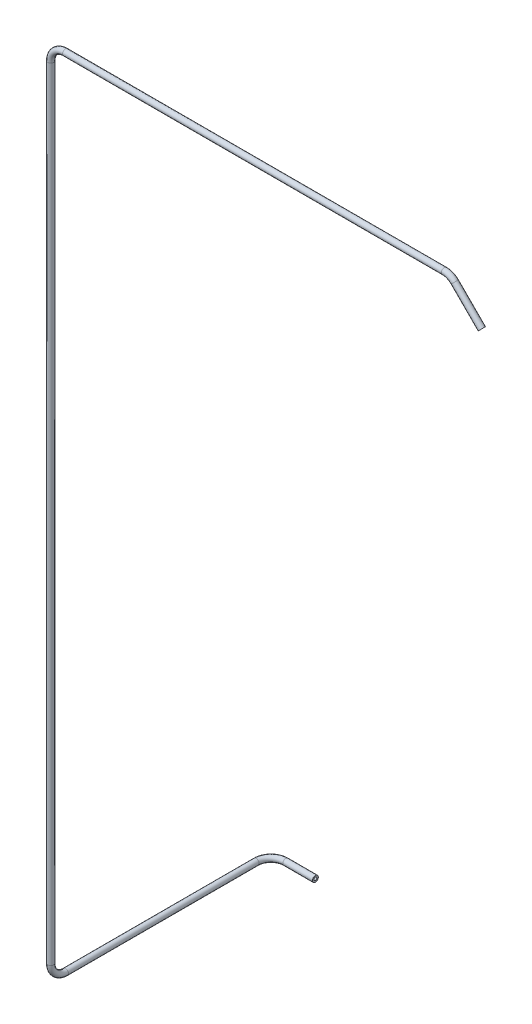
SolidWorks part; units mm, degrees
ref_plane "Front Plane" through (0, 0, 0) normal (0, 0, 1) x (1, 0, 0)
ref_plane "Top Plane" through (0, 0, 0) normal (0, 1, 0) x (1, 0, 0)
ref_plane "Right Plane" through (0, 0, 0) normal (1, 0, 0) x (0, 0, -1)
sketch "Sketch1" plane through (0, 0, 0) normal (0, 0, 1) x (1, 0, 0)
  line L0 (0, 0) -> (-21.2132, 21.2132)
  line L1 (-21.2132, 21.2132) -> (-291.2132, 21.2132)
  line L2 (-291.2132, 21.2132) -> (-291.2132, -526.7068)
  line L3 (0, 0) -> (0, 31.3965) construction
  point P3 (0, 0)
  point P7 (0, 0)
  point P8 (0, 0)
  point P9 (0, 0)
  dimension "D1" = 45
  dimension "D2" = 30
  dimension "D3" = 270
  dimension "D4" = 547.92
ref_plane "Plane1" through (0, -526.7068, 0) normal (0, 1, 0) x (1, 0, 0)
sketch "Sketch2" plane through (0, -526.7068, 0) normal (0, 1, 0) x (1, 0, 0)
  line L0 (-291.2132, 0) -> (-291.2132, 148.77)
  line L1 (-21.2132, 0) -> (-291.2132, 0) construction
  line L2 (-291.2132, 148.77) -> (-261.2132, 148.77)
  dimension "D1" = 148.77
  dimension "D2" = 30
sketch3d "3DSketch1"
  line L0 (0, 0, 0) -> (-18.2843, 18.2843, 0)
  line L1 (-25.3553, 21.2132, 0) -> (-281.2132, 21.2132, 0)
  line L2 (-291.2132, 11.2132, 0) -> (-291.2132, -516.7068, 0)
  line L3 (-291.2132, -526.7068, -10) -> (-291.2132, -526.7068, -138.77)
  line L4 (-281.2132, -526.7068, -148.77) -> (-261.2132, -526.7068, -148.77)
  arc A0 (-291.2132, -526.7068, -138.77) -> (-281.2132, -526.7068, -148.77) centre (-281.2132, -526.7068, -138.77) ccw
  arc A1 (-291.2132, -516.7068, 0) -> (-291.2132, -526.7068, -10) centre (-291.2132, -516.7068, -10) ccw
  arc A2 (-281.2132, 21.2132, 0) -> (-291.2132, 11.2132, 0) centre (-281.2132, 11.2132, 0) ccw
  arc A3 (-18.2843, 18.2843, 0) -> (-25.3553, 21.2132, 0) centre (-25.3553, 11.2132, 0) ccw
  point P14 (-291.2132, -526.7068, -148.77)
  point P15 (-281.2132, -536.7068, -138.77)
  point P18 (-291.2132, -526.7068, 0)
  point P19 (-281.2132, -516.7068, -10)
  point P22 (-291.2132, 21.2132, 0)
  point P23 (-281.2132, 11.2132, 10)
  point P26 (-21.2132, 21.2132, 0)
  point P27 (-25.3553, 11.2132, 10)
  dimension "D1" = 10
ref_plane "Plane2" through (0, 0, 0) normal (-0.7071, 0.7071, 0) x (0, 0, 1)
sketch "Sketch4" plane through (0, 0, 0) normal (-0.7071, 0.7071, 0) x (0, 0, 1)
  circle A0 centre (0, 0) radius 1
  circle A1 centre (0, 0) radius 2
  dimension "D1" = 2
  dimension "D2" = 4
sweep "Sweep2" add profiles "Sketch4" path "3DSketch1"
